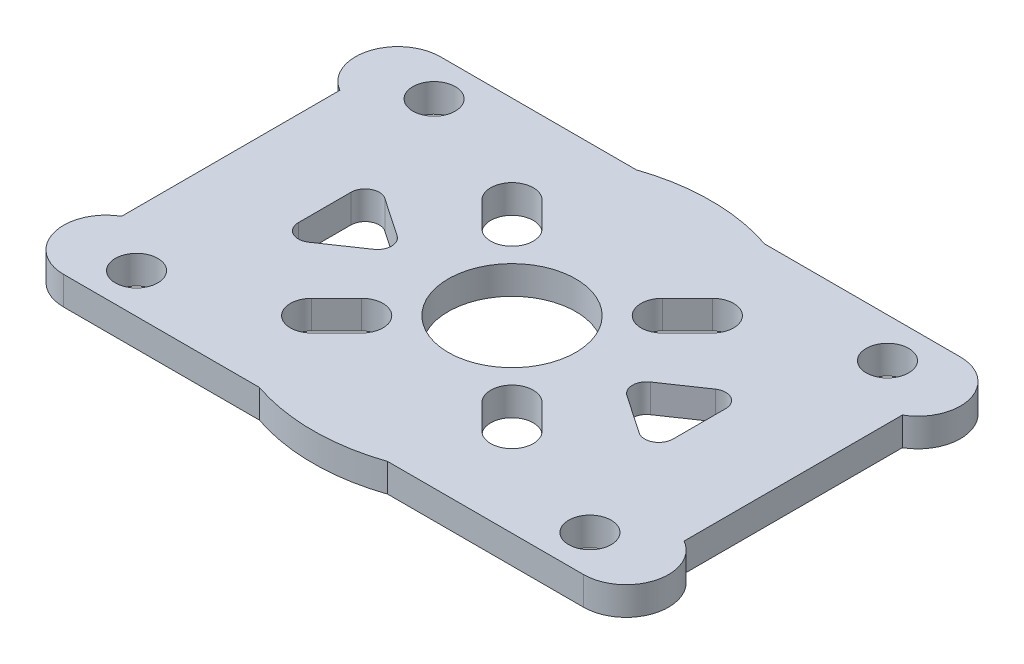
SolidWorks part; units mm, degrees
material "Thornel Mat VMA"
ref_plane "Front Plane" through (0, 0, 0) normal (0, 0, 1) x (1, 0, 0)
ref_plane "Top Plane" through (0, 0, 0) normal (0, 1, 0) x (1, 0, 0)
ref_plane "Right Plane" through (0, 0, 0) normal (1, 0, 0) x (0, 0, -1)
sketch "Sketch1" plane through (0, 0, 0) normal (0, 1, 0) x (1, 0, 0)
  line L0 (0, -55) -> (0, 55) construction
  line L1 (-18.35, -13.3) -> (-4.5291, -13.3)
  line L2 (-21.35, -10.3) -> (-21.35, 10.3) construction
  line L3 (-18.35, 13.3) -> (-4.5291, 13.3)
  line L4 (21.35, -10.3) -> (21.35, 10.3) construction
  line L5 (-55, 0) -> (55, 0) construction
  line L10 (-7.0711, 7.0711) -> (-5.3033, 5.3033) construction
  line L11 (-6.0104, 8.1317) -> (-4.2426, 6.364)
  line L12 (-8.1317, 6.0104) -> (-6.364, 4.2426)
  line L13 (7.0711, 7.0711) -> (5.3033, 5.3033) construction
  line L14 (8.1317, 6.0104) -> (6.364, 4.2426)
  line L15 (6.0104, 8.1317) -> (4.2426, 6.364)
  line L16 (7.0711, -7.0711) -> (5.3033, -5.3033) construction
  line L17 (6.0104, -8.1317) -> (4.2426, -6.364)
  line L18 (8.1317, -6.0104) -> (6.364, -4.2426)
  line L19 (-7.0711, -7.0711) -> (-5.3033, -5.3033) construction
  line L20 (-8.1317, -6.0104) -> (-6.364, -4.2426)
  line L21 (-6.0104, -8.1317) -> (-4.2426, -6.364)
  line L22 (4.5291, 13.3) -> (18.35, 13.3)
  line L23 (-19.85, 7.7019) -> (-19.85, -7.7019)
  line L24 (4.5291, -13.3) -> (18.35, -13.3)
  line L25 (19.85, 7.7019) -> (19.85, -7.7019)
  line L26 (-13.2249, 1.8579) -> (-13.2249, -1.8579)
  line L27 (-11.6615, -2.6841) -> (-8.9367, -0.8262)
  line L28 (-8.9367, 0.8262) -> (-11.6615, 2.6841)
  line L29 (11.6615, -2.6841) -> (8.9367, -0.8262)
  line L30 (13.2249, 1.8579) -> (13.2249, -1.8579)
  line L31 (8.9367, 0.8262) -> (11.6615, 2.6841)
  circle A0 centre (-16, 10.5) radius 1.5
  circle A1 centre (-16, -10.5) radius 1.5
  circle A2 centre (16, -10.5) radius 1.5
  circle A3 centre (16, 10.5) radius 1.5
  circle A4 centre (0, 0) radius 4.5
  arc A5 (-6.0104, 8.1317) -> (-8.1317, 6.0104) centre (-7.0711, 7.0711) ccw
  arc A6 (-6.364, 4.2426) -> (-4.2426, 6.364) centre (-5.3033, 5.3033) ccw
  arc A7 (8.1317, 6.0104) -> (6.0104, 8.1317) centre (7.0711, 7.0711) ccw
  arc A8 (4.2426, 6.364) -> (6.364, 4.2426) centre (5.3033, 5.3033) ccw
  arc A9 (6.0104, -8.1317) -> (8.1317, -6.0104) centre (7.0711, -7.0711) ccw
  arc A10 (6.364, -4.2426) -> (4.2426, -6.364) centre (5.3033, -5.3033) ccw
  arc A11 (-8.1317, -6.0104) -> (-6.0104, -8.1317) centre (-7.0711, -7.0711) ccw
  arc A12 (-4.2426, -6.364) -> (-6.364, -4.2426) centre (-5.3033, -5.3033) ccw
  arc A14 (4.5291, 13.3) -> (-4.5291, 13.3) centre (0, 0) ccw
  arc A15 (-4.5291, -13.3) -> (4.5291, -13.3) centre (0, 0) ccw
  arc A16 (-8.9367, 0.8262) -> (-8.9367, -0.8262) centre (-9.5, 0) cw
  arc A17 (-11.6615, -2.6841) -> (-13.2249, -1.8579) centre (-12.2249, -1.8579) cw
  arc A18 (-11.6615, 2.6841) -> (-13.2249, 1.8579) centre (-12.2249, 1.8579) ccw
  arc A19 (11.6615, -2.6841) -> (13.2249, -1.8579) centre (12.2249, -1.8579) ccw
  arc A20 (8.9367, 0.8262) -> (8.9367, -0.8262) centre (9.5, 0) ccw
  arc A21 (11.6615, 2.6841) -> (13.2249, 1.8579) centre (12.2249, 1.8579) cw
  arc A22 (-18.35, 13.3) -> (-19.85, 7.7019) centre (-18.35, 10.3) ccw
  arc A23 (-19.85, -7.7019) -> (-18.35, -13.3) centre (-18.35, -10.3) ccw
  arc A24 (19.85, 7.7019) -> (18.35, 13.3) centre (18.35, 10.3) ccw
  arc A25 (18.35, -13.3) -> (19.85, -7.7019) centre (18.35, -10.3) ccw
  point P8 (21.35, 0)
  point P23 (-6.1872, 6.1872)
  point P33 (6.1872, 6.1872)
  point P40 (6.1872, -6.1872)
  point P47 (-6.1872, -6.1872)
  point P52 (0, 0)
  point P55 (-13.2249, 0)
  point P60 (-7.7249, 0)
  point P63 (-13.2249, -3.75)
  point P66 (-13.2249, 3.75)
  dimension "D4" = 3
  dimension "D5" = 9
  dimension "D11" = 14.05
  dimension "D14" = 1
  dimension "D20" = 3
  dimension "D6" = 3
  dimension "D7" = 2.5
  dimension "D8" = 7.5
  dimension "D9" = 45
  dimension "D12" = 7.5
  dimension "D13" = 5.5
  dimension "D15" = 9.5
  dimension "D3" = 32
  dimension "D16" = 16
  dimension "D17" = 21
  dimension "D18" = 10.5
  dimension "D19" = 21.35
  dimension "D21" = 3
  dimension "D22" = 3
  dimension "D23" = 26.6
  dimension "D24" = 21.35
  dimension "D10" = 4
extrude "Boss-Extrude1" add sketch "Sketch1" along normal blind 2
